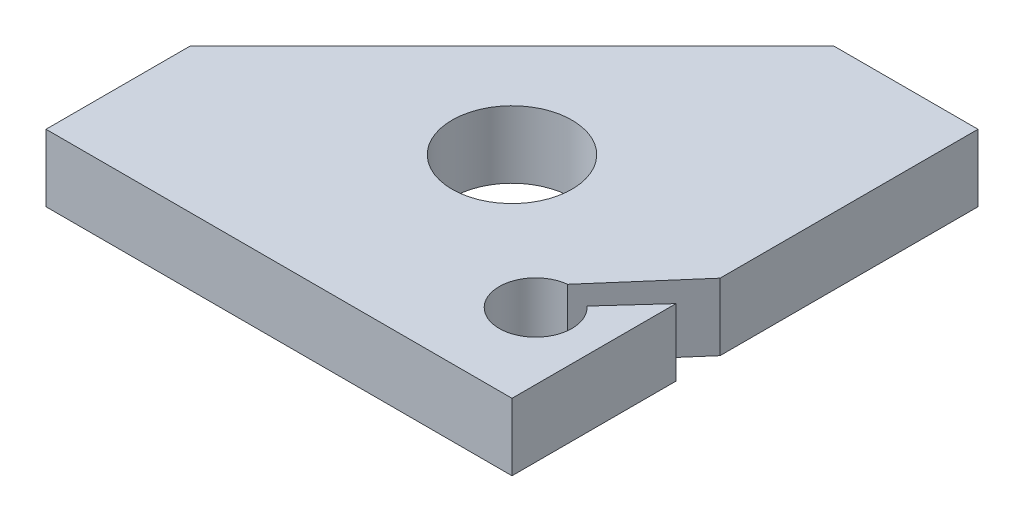
SolidWorks part; units mm, degrees
ref_plane "Front Plane" through (0, 0, 0) normal (0, 0, 1) x (1, 0, 0)
ref_plane "Top Plane" through (0, 0, 0) normal (0, 1, 0) x (1, 0, 0)
ref_plane "Right Plane" through (0, 0, 0) normal (1, 0, 0) x (0, 0, -1)
sketch "Sketch1" plane through (0, 0, 0) normal (0, 1, 0) x (1, 0, 0)
  line L32 (72.34, -63.4052) -> (38.75, -96.9952)
  line L33 (38.75, -111.9952) -> (87.34, -111.9952)
  line L35 (72.34, -63.4052) -> (87.34, -63.4052)
  line L36 (38.75, -96.9952) -> (38.75, -111.9952)
  line L37 (87.34, -90.2963) -> (79.9488, -98.7989)
  line L38 (82.9227, -99.7601) -> (87.34, -94.8963)
  line L39 (87.34, -90.2963) -> (87.34, -63.4052)
  line L40 (87.34, -94.8963) -> (87.34, -111.9952)
  circle A2 centre (65.34, -89.9952) radius 6.25
  arc A3 (79.9488, -98.7989) -> (82.9227, -99.7601) centre (80.3729, -102.5677) ccw
  dimension "D13" = 12.5
  dimension "D2" = 4.6
  dimension "D8" = 15
extrude "Boss-Extrude1" add sketch "Sketch1" along normal blind 7
